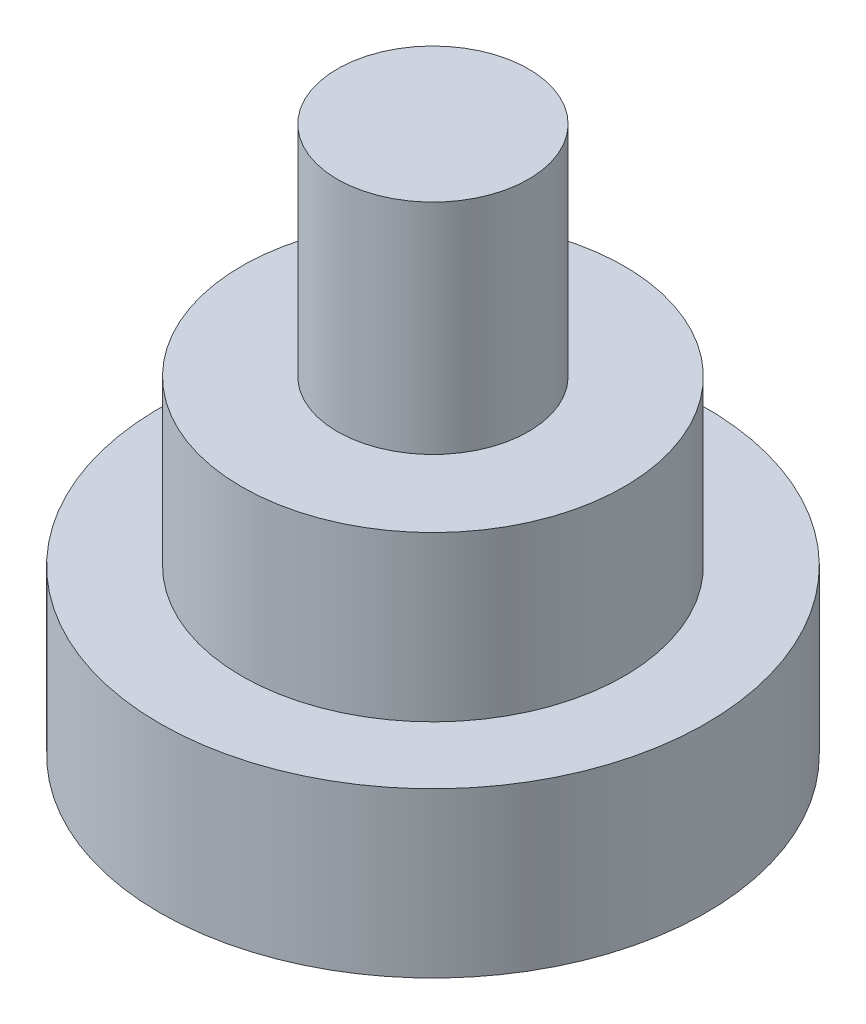
SolidWorks part; units mm, degrees
ref_plane "Front Plane" through (0, 0, 0) normal (0, 0, 1) x (1, 0, 0)
ref_plane "Top Plane" through (0, 0, 0) normal (0, 1, 0) x (1, 0, 0)
ref_plane "Right Plane" through (0, 0, 0) normal (1, 0, 0) x (0, 0, -1)
sketch "Sketch2" plane through (0, 0, 0) normal (0, 1, 0) x (1, 0, 0)
  circle A0 centre (0, 0) radius 5
  dimension "D1" = 10
extrude "Boss-Extrude1" add sketch "Sketch2" along normal blind 3
sketch "Sketch3" plane through (0, 3, 0) normal (0, 1, 0) x (1, 0, 0)
  circle A0 centre (0, 0) radius 3.5
  dimension "D1" = 7
extrude "Boss-Extrude2" add sketch "Sketch3" along normal blind 3
sketch "Sketch4" plane through (0, 6, 0) normal (0, 1, 0) x (1, 0, 0)
  circle A0 centre (0, 0) radius 1.75
  dimension "D1" = 3.5
extrude "Boss-Extrude3" add sketch "Sketch4" along normal blind 4
sketch "Sketch6" plane through (0, 0, 0) normal (0, -1, 0) x (-1, 0, 0)
  circle A0 centre (0, 0) radius 4
  dimension "D1" = 8
extrude "Cut-Extrude1" cut sketch "Sketch6" against normal blind 1.5
